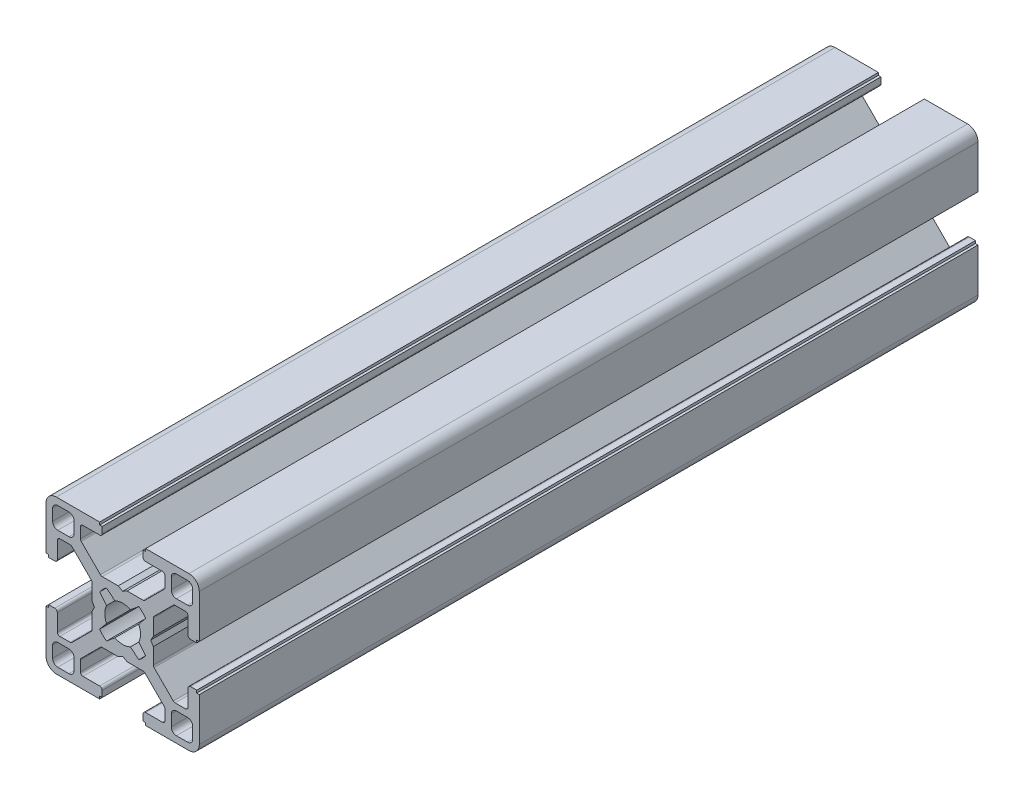
SolidWorks part; units mm, degrees
ref_plane "Front Plane" through (0, 0, 0) normal (0, 0, 1) x (1, 0, 0)
ref_plane "Top Plane" through (0, 0, 0) normal (0, 1, 0) x (1, 0, 0)
ref_plane "Right Plane" through (0, 0, 0) normal (1, 0, 0) x (0, 0, -1)
sketch "Sketch1" plane through (0, 0, 0) normal (0, 0, 1) x (1, 0, 0)
  line L0 (-15, 0) -> (15, 0) construction
  line L1 (0, -15) -> (0, 15) construction
  line L2 (-4.5, 15) -> (4.5, 15) construction
  line L3 (-4, -15) -> (4, -15) construction
  line L4 (-4.5, 15) -> (-4.5, 14.5)
  line L5 (-4.5, 14.5) -> (-4, 14.5)
  line L6 (-4, 14.5) -> (-4, 13.29)
  line L7 (-4.5, 12.79) -> (-7.7675, 12.79)
  line L8 (-8.2675, 12.29) -> (-8.2675, 10.2707)
  line L9 (-8.1211, 9.9171) -> (-4.3504, 6.1464)
  line L10 (-3.9968, 6) -> (0, 6)
  line L11 (0, 0) -> (-15, 15) construction
  line L12 (-4.5, 15) -> (-12.968, 15)
  line L14 (-12.705, 9.5135) -> (-10.5135, 9.5135)
  line L15 (-13.705, 10.5135) -> (-13.705, 12.705)
  line L16 (-12.705, 13.705) -> (-10.5135, 13.705)
  line L17 (-9.5135, 10.5135) -> (-9.5135, 12.705)
  line L18 (-13.705, 9.5135) -> (-9.5135, 13.705) construction
  line L19 (-13.705, 13.705) -> (-9.5135, 9.5135) construction
  line L20 (-3.1568, 4.5038) -> (-1.5303, 3.1477) construction
  line L21 (-4.5038, 3.1568) -> (-3.1477, 1.5303) construction
  line L22 (-6, 3.9968) -> (-6, 0)
  line L23 (-9.9171, 8.1211) -> (-6.1464, 4.3504)
  line L24 (-15, 4.5) -> (-15, 12.968)
  line L25 (-12.29, 8.2675) -> (-10.2707, 8.2675)
  line L26 (-12.79, 4.5) -> (-12.79, 7.7675)
  line L27 (-14.5, 4) -> (-13.29, 4)
  line L28 (-14.5, 4.5) -> (-14.5, 4)
  line L29 (-15, 4.5) -> (-14.5, 4.5)
  circle A0 centre (0, 0) radius 3.5
  arc A1 (-12.968, 15) -> (-15, 12.968) centre (-12.968, 12.968) ccw
  circle A2 centre (0, 0) radius 5.5 construction
  arc A3 (-10.5135, 9.5135) -> (-9.5135, 10.5135) centre (-10.5135, 10.5135) ccw
  arc A4 (-13.705, 12.705) -> (-12.705, 13.705) centre (-12.705, 12.705) cw
  arc A5 (-10.5135, 13.705) -> (-9.5135, 12.705) centre (-10.5135, 12.705) cw
  arc A6 (-12.705, 9.5135) -> (-13.705, 10.5135) centre (-12.705, 10.5135) cw
  arc A7 (-12.79, 4.5) -> (-13.29, 4) centre (-13.29, 4.5) cw
  arc A8 (-12.29, 8.2675) -> (-12.79, 7.7675) centre (-12.29, 7.7675) ccw
  arc A9 (-9.9171, 8.1211) -> (-10.2707, 8.2675) centre (-10.2707, 7.7675) ccw
  arc A10 (-6, 3.9968) -> (-6.1464, 4.3504) centre (-6.5, 3.9968) ccw
  arc A11 (-4.3504, 6.1464) -> (-3.9968, 6) centre (-3.9968, 6.5) ccw
  arc A12 (-4, 13.29) -> (-4.5, 12.79) centre (-4.5, 13.29) cw
  arc A13 (-7.7675, 12.79) -> (-8.2675, 12.29) centre (-7.7675, 12.29) ccw
  arc A14 (-8.2675, 10.2707) -> (-8.1211, 9.9171) centre (-7.7675, 10.2707) ccw
  point P4 (0, 0)
  point P8 (0, 0)
  point P13 (0, 15)
  point P15 (0, -15)
  point P16 (0, 6)
  point P23 (-11.6092, 11.6093)
  point P26 (0, 6)
  point P62 (-12.79, 4)
  point P65 (-12.79, 8.2675)
  point P68 (-10.0636, 8.2675)
  point P71 (-6, 4.2039)
  point P74 (-4.2039, 6)
  point P77 (-4, 12.79)
  point P80 (-8.2675, 12.79)
  point P83 (-8.2675, 10.0636)
  dimension "Center Hole Diameter" = 7
  dimension "D11" = 2.032
  dimension "D9" = 11
  dimension "D13" = 1
  dimension "D14" = 0.5
  dimension "Rail Height" = 30
  dimension "Rail Width" = 30
  dimension "T-Slot Width" = 8
  dimension "T-Slot Depth" = 9
  dimension "D1" = 9
  dimension "D2" = 45
  dimension "D3" = 8
  dimension "D4" = 2.21
  dimension "D5" = 16.535
  dimension "D7" = 2.54
  dimension "D6" = 1.295
  dimension "D8" = 1.246
  dimension "D10" = 10.36
  dimension "D12" = 1.905
sketch "Sketch2" plane through (0, 0, 0) normal (1, 0, 0) x (0, 0, -1)
  line L0 (-76.2, 0) -> (76.2, 0) construction
  line L2 (0, -15) -> (0, 15) construction
  line L3 (0, -15) -> (0, 15) construction
  line L4 (-76.2, -15) -> (-76.2, 15) construction
  line L5 (76.2, -15) -> (76.2, 15) construction
  point P0 (-38.7, 0)
  point P3 (0, 0)
  point P4 (38.7, 0)
  point P12 (-76.2, 0)
  point P14 (76.2, 0)
  dimension "Length" = 152.4
  dimension "D1" = 37.5
sketch "Sketch3" plane through (0, 0, 0) normal (0, 0, 1) x (1, 0, 0)
  line L0 (-4.5038, 3.1568) -> (-3.1477, 1.5303)
  line L1 (0, 3.5) -> (0, 5.5)
  line L2 (-5.5, 0) -> (-3.5, 0)
  line L7 (-6, 3.9968) -> (-6, 0) construction
  line L31 (-9.9171, 8.1211) -> (-6.1464, 4.3504) construction
  line L117 (-12.29, 8.2675) -> (-10.2707, 8.2675) construction
  line L118 (-12.79, 4.5) -> (-12.79, 7.7675) construction
  line L157 (-12.705, 9.5135) -> (-10.5135, 9.5135)
  line L158 (-9.5135, 10.5135) -> (-9.5135, 12.705)
  line L163 (-10.5135, 13.705) -> (-12.705, 13.705)
  line L164 (-13.705, 12.705) -> (-13.705, 10.5135)
  line L165 (-12.705, 9.5135) -> (-10.5135, 9.5135)
  line L166 (-9.5135, 10.5135) -> (-9.5135, 12.705)
  line L167 (-10.5135, 13.705) -> (-12.705, 13.705)
  line L168 (-13.705, 12.705) -> (-13.705, 10.5135)
  line L169 (-14.5, 4) -> (-13.29, 4) construction
  line L170 (-14.5, 4.5) -> (-14.5, 4) construction
  line L171 (-15, 4.5) -> (-14.5, 4.5) construction
  line L172 (-15, 4.5) -> (-15, 12.968) construction
  line L173 (-4.5, 15) -> (-12.968, 15) construction
  line L174 (-4.5, 15) -> (-4.5, 14.5) construction
  line L175 (-4.5, 14.5) -> (-4, 14.5) construction
  line L176 (-4, 14.5) -> (-4, 13.29) construction
  line L177 (-4.5, 12.79) -> (-7.7675, 12.79) construction
  line L178 (-8.2675, 12.29) -> (-8.2675, 10.2707) construction
  line L179 (-8.1211, 9.9171) -> (-4.3504, 6.1464) construction
  line L180 (-3.9968, 6) -> (0, 6) construction
  line L181 (-6, 3.9968) -> (-6, 0.866)
  line L182 (-9.9171, 8.1211) -> (-6.1464, 4.3504)
  line L183 (-12.29, 8.2675) -> (-10.2707, 8.2675)
  line L184 (-12.79, 4.5) -> (-12.79, 7.7675)
  line L185 (-14.5, 4) -> (-13.29, 4)
  line L186 (-14.5, 4.5) -> (-14.5, 4)
  line L187 (-15, 4.5) -> (-14.5, 4.5)
  line L188 (-15, 4.5) -> (-15, 12.968)
  line L189 (-4.5, 15) -> (-12.968, 15)
  line L190 (-4.5, 15) -> (-4.5, 14.5)
  line L191 (-4.5, 14.5) -> (-4, 14.5)
  line L192 (-4, 14.5) -> (-4, 13.29)
  line L193 (-4.5, 12.79) -> (-7.7675, 12.79)
  line L194 (-8.2675, 12.29) -> (-8.2675, 10.2707)
  line L195 (-8.1211, 9.9171) -> (-4.3504, 6.1464)
  line L196 (-3.9968, 6) -> (-0.866, 6)
  line L197 (-0.866, 6) -> (0, 5.5)
  line L198 (0, -15) -> (0, 15) construction
  line L199 (0, 0) -> (-15, 15) construction
  line L200 (0, 0) -> (-15, 15) construction
  line L201 (-3.1568, 4.5038) -> (-1.5303, 3.1477) construction
  line L202 (-3.1568, 4.5038) -> (-1.5303, 3.1477)
  line L203 (-6, 0.866) -> (-5.5, 0)
  line L204 (-15, 0) -> (15, 0) construction
  line L205 (-15, 0) -> (15, 0) construction
  line L206 (0, -15) -> (0, 15) construction
  arc A0 (-3.5, 0) -> (-3.1477, 1.5303) centre (0, 0) cw
  arc A10 (-6, 3.9968) -> (-6.1464, 4.3504) centre (-6.5, 3.9968) ccw construction
  circle A16 centre (0, 0) radius 3.5
  arc A18 (0, 3.5) -> (-1.5303, 3.1477) centre (0, 0) ccw
  arc A20 (-9.9171, 8.1211) -> (-10.2707, 8.2675) centre (-10.2707, 7.7675) ccw construction
  arc A22 (-12.29, 8.2675) -> (-12.79, 7.7675) centre (-12.29, 7.7675) ccw construction
  arc A28 (-13.29, 4) -> (-12.79, 4.5) centre (-13.29, 4.5) ccw construction
  arc A29 (-10.5135, 9.5135) -> (-9.5135, 10.5135) centre (-10.5135, 10.5135) ccw
  arc A30 (-9.5135, 12.705) -> (-10.5135, 13.705) centre (-10.5135, 12.705) ccw
  arc A31 (-12.705, 13.705) -> (-13.705, 12.705) centre (-12.705, 12.705) ccw
  arc A32 (-13.705, 10.5135) -> (-12.705, 9.5135) centre (-12.705, 10.5135) ccw
  arc A33 (-10.5135, 9.5135) -> (-9.5135, 10.5135) centre (-10.5135, 10.5135) ccw
  arc A34 (-9.5135, 12.705) -> (-10.5135, 13.705) centre (-10.5135, 12.705) ccw
  arc A35 (-12.705, 13.705) -> (-13.705, 12.705) centre (-12.705, 12.705) ccw
  arc A36 (-13.705, 10.5135) -> (-12.705, 9.5135) centre (-12.705, 10.5135) ccw
  arc A37 (-12.968, 15) -> (-15, 12.968) centre (-12.968, 12.968) ccw construction
  arc A38 (-4.5, 12.79) -> (-4, 13.29) centre (-4.5, 13.29) ccw construction
  arc A39 (-7.7675, 12.79) -> (-8.2675, 12.29) centre (-7.7675, 12.29) ccw construction
  arc A40 (-8.2675, 10.2707) -> (-8.1211, 9.9171) centre (-7.7675, 10.2707) ccw construction
  arc A41 (-4.3504, 6.1464) -> (-3.9968, 6) centre (-3.9968, 6.5) ccw construction
  arc A42 (-6, 3.9968) -> (-6.1464, 4.3504) centre (-6.5, 3.9968) ccw
  arc A43 (-9.9171, 8.1211) -> (-10.2707, 8.2675) centre (-10.2707, 7.7675) ccw
  arc A44 (-12.29, 8.2675) -> (-12.79, 7.7675) centre (-12.29, 7.7675) ccw
  arc A45 (-13.29, 4) -> (-12.79, 4.5) centre (-13.29, 4.5) ccw
  arc A46 (-12.968, 15) -> (-15, 12.968) centre (-12.968, 12.968) ccw
  arc A47 (-4.5, 12.79) -> (-4, 13.29) centre (-4.5, 13.29) ccw
  arc A48 (-7.7675, 12.79) -> (-8.2675, 12.29) centre (-7.7675, 12.29) ccw
  arc A49 (-8.2675, 10.2707) -> (-8.1211, 9.9171) centre (-7.7675, 10.2707) ccw
  arc A50 (-4.3504, 6.1464) -> (-3.9968, 6) centre (-3.9968, 6.5) ccw
  circle A51 centre (0, 0) radius 5.5 construction
  arc A52 (-3.1568, 4.5038) -> (-4.5038, 3.1568) centre (0, 0) ccw
  dimension "D3" = 60
  dimension "D4" = 60
  dimension "D1" = 0
  dimension "D2" = 0
extrude "Boss-Extrude1" add sketch "Sketch3" along normal mid plane 152.4
pattern_circular "CirPattern1" count 4 over 360 about axis through (0, 0, 0) along (0, 0, 1) of "Boss-Extrude1"
ref_plane "Contact Plane1" through (15, 0, 0) normal (1, 0, 0) x (0, 0, -1)
ref_plane "Contact Plane2" through (0, -15, 0) normal (0, 1, 0) x (1, 0, 0)
ref_plane "Contact Plane3" through (-15, 0, 0) normal (1, 0, 0) x (0, 0, -1)
ref_plane "Contact Plane4" through (0, 15, 0) normal (0, 1, 0) x (1, 0, 0)
equation "\"D1@Sketch2\" = \"Rail Height@Sketch1\" * 1.25"
equation "\"D1@Sketch1\"=\"T-Slot Width@Sketch1\"+1mm"
equation "\"D3@Sketch1\"=\"T-Slot Width@Sketch1\""
equation "\"D1@Boss-Extrude1\"=\"Length\""
equation "\"Length\"= 6in"
